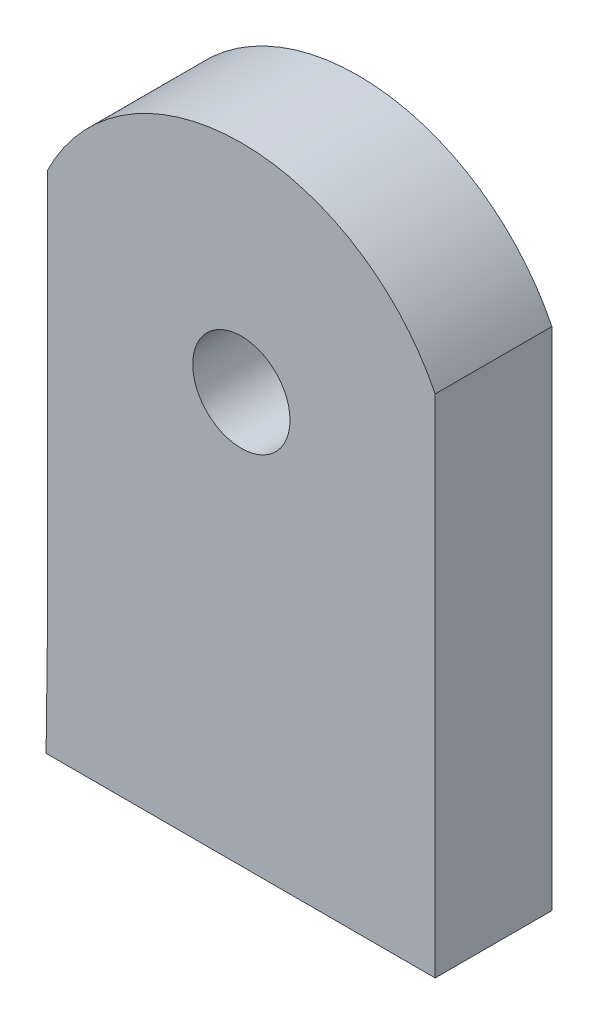
SolidWorks part; units mm, degrees
ref_plane "Front Plane" through (0, 0, 0) normal (0, 0, 1) x (1, 0, 0)
ref_plane "Top Plane" through (0, 0, 0) normal (0, 1, 0) x (1, 0, 0)
ref_plane "Right Plane" through (0, 0, 0) normal (1, 0, 0) x (0, 0, -1)
sketch "Sketch1" plane through (0, 0, 0) normal (0, 0, 1) x (1, 0, 0)
  line L1 (-5.4719, 56.6688) -> (-5.4719, 53.1368) construction
  line L6 (-10.4532, 49.1213) -> (-10.4907, 46.1215)
  line L7 (-10.4907, 46.1215) -> (-0.4907, 46.1215)
  line L10 (-0.4907, 49.1215) -> (-0.4907, 46.1215)
  line L12 (-0.4907, 59.1213) -> (-0.4907, 49.1215)
  line L14 (-10.4532, 59.1213) -> (-10.4532, 49.1213)
  circle A0 centre (-5.4719, 56.6688) radius 1.25
  arc A1 (-0.4907, 59.1213) -> (-10.4532, 59.1213) centre (-5.4719, 56.6688) ccw
  dimension "D1" = 2.5
  dimension "D2" = 2.9998
  dimension "D4" = 5.5523
  dimension "D3" = 10
  dimension "D5" = 3
  dimension "D6" = 10
extrude "Boss-Extrude1" add sketch "Sketch1" along normal blind 3
